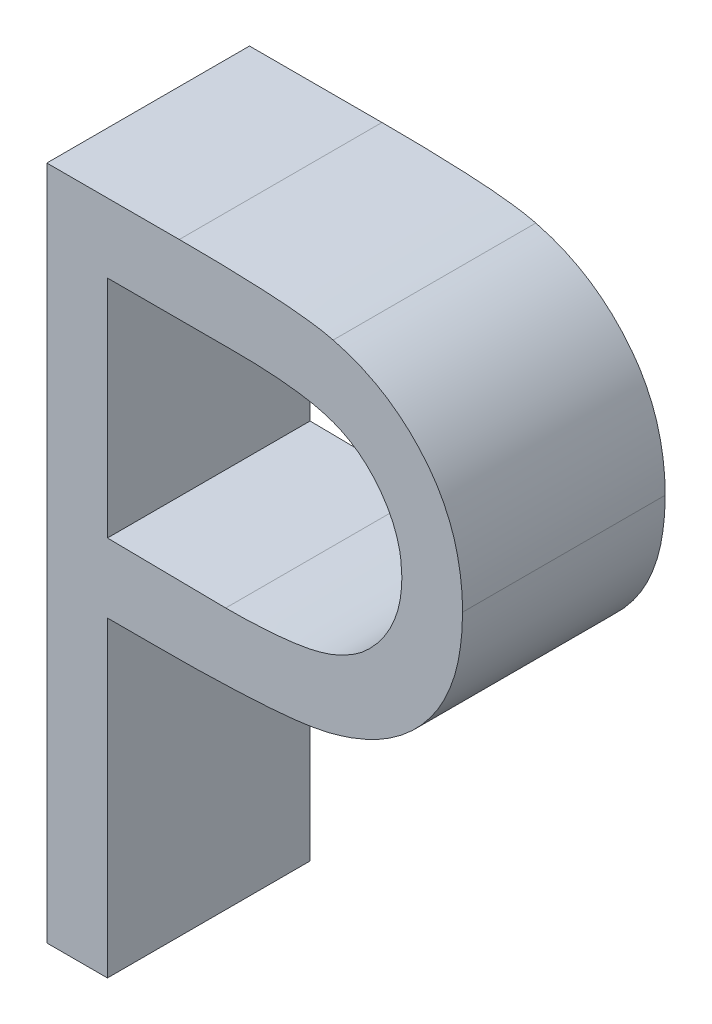
SolidWorks part; units mm, degrees
ref_plane "Plan de face" through (0, 0, 0) normal (0, 0, 1) x (1, 0, 0)
ref_plane "Plan de dessus" through (0, 0, 0) normal (0, 1, 0) x (1, 0, 0)
ref_plane "Plan de droite" through (0, 0, 0) normal (1, 0, 0) x (0, 0, -1)
sketch "Esquisse1" plane through (0, 0, 0) normal (0, 0, 1) x (1, 0, 0)
  text T0 "P" font "Century Gothic" height 5
extrude "Boss.-Extru.1" add sketch "Esquisse1" along normal blind 1.5
